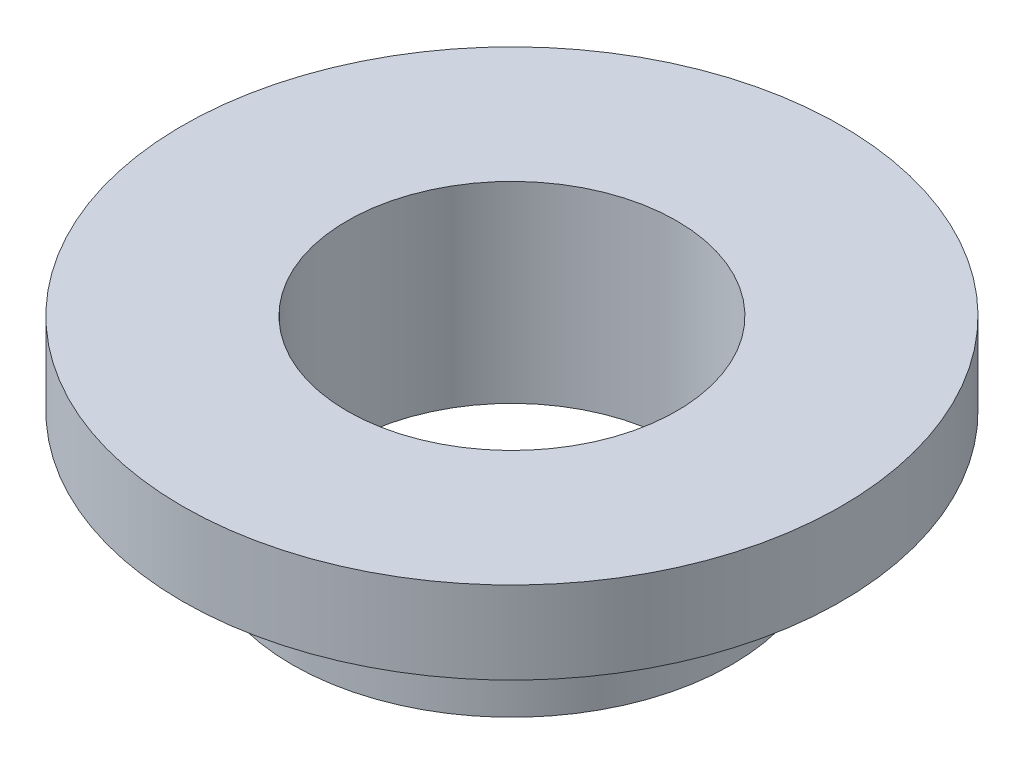
SolidWorks part; units mm, degrees
ref_plane "Спереди" through (0, 0, 0) normal (0, 0, 1) x (1, 0, 0)
ref_plane "Сверху" through (0, 0, 0) normal (0, 1, 0) x (1, 0, 0)
ref_plane "Справа" through (0, 0, 0) normal (1, 0, 0) x (0, 0, -1)
sketch "Эскиз1" plane through (0, 0, 0) normal (0, 1, 0) x (1, 0, 0)
  circle A0 centre (0, 0) radius 6
  circle A1 centre (0, 0) radius 8
  dimension "D1" = 12
  dimension "D2" = 16
extrude "Вытянуть1" add sketch "Эскиз1" along normal blind 4
sketch "Эскиз2" plane through (0, 4, 0) normal (0, 1, 0) x (-1, 0, 0)
  circle A0 centre (0, 0) radius 12
  circle A1 centre (0, 0) radius 6
  dimension "D1" = 12
  dimension "D2" = 24
extrude "Вытянуть2" add sketch "Эскиз2" along normal blind 3
